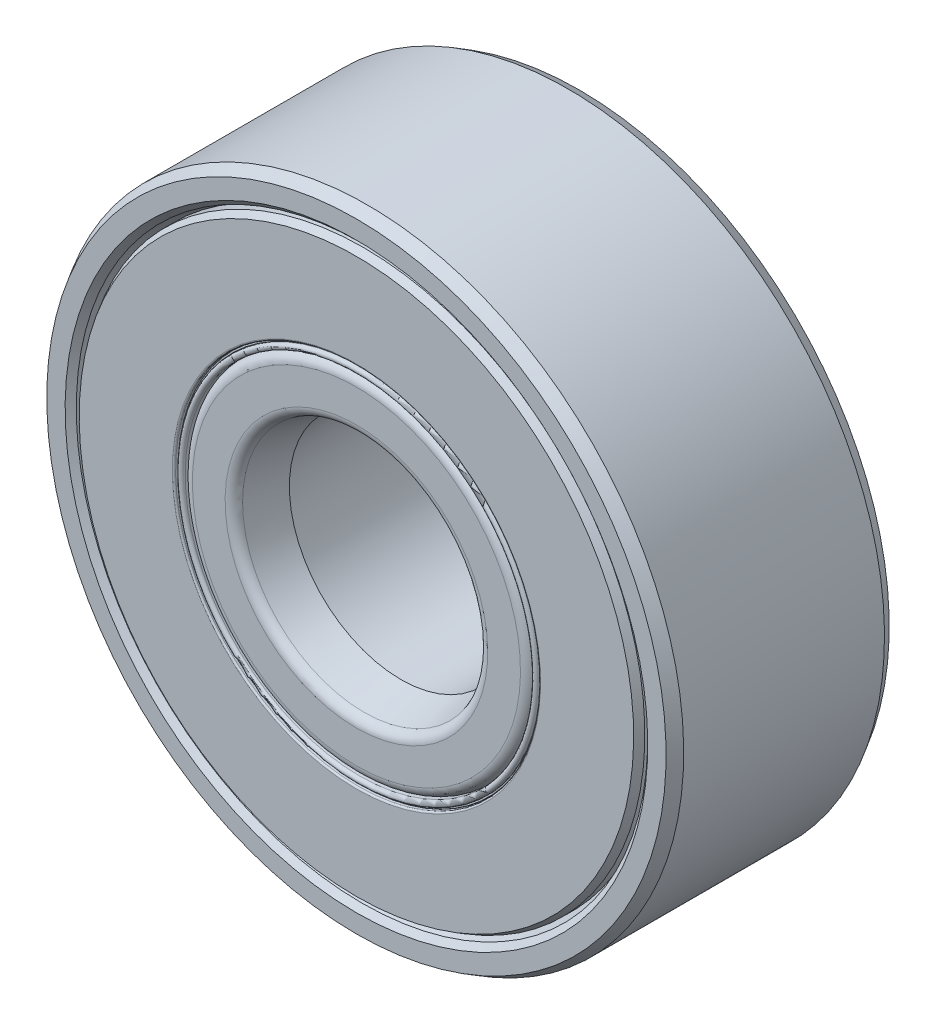
SolidWorks part; units mm, degrees
ref_plane "Front Plane" through (0, 0, 0) normal (0, 0, 1) x (1, 0, 0)
ref_plane "Top Plane" through (0, 0, 0) normal (0, 1, 0) x (1, 0, 0)
ref_plane "Right Plane" through (0, 0, 0) normal (1, 0, 0) x (0, 0, -1)
sketch "Sketch1" plane through (0, 0, 0) normal (0, 0, 1) x (1, 0, 0)
  line L0 (-8.5, 0) -> (8.5, 0) construction
  line L1 (-3, 0) -> (3, 0) construction
  circle A0 centre (0, 0) radius 3 construction
  circle A1 centre (0, 0) radius 8.5 construction
  point P3 (0, 0)
  point P6 (0, 0)
  point P7 (0, -3)
  point P11 (0, -8.5)
  point P12 (0, 3)
  point P13 (0, 8.5)
  dimension "OD" = 17
  dimension "ID" = 6
sketch "Sketch2" plane through (0, 0, 0) normal (1, 0, 0) x (0, 0, -1)
  line L0 (-3, 8.5) -> (3, 8.5) construction
  line L1 (0, 8.5) -> (0, -8.5) construction
  line L2 (2.7, 8.5) -> (-2.7, 8.5)
  line L3 (-2.7, 8.5) -> (-3, 8.3268)
  line L4 (-3, 8.3268) -> (-3, 7.8335)
  line L5 (-2.5245, 7.565) -> (-1.4774, 7.565)
  line L6 (2.5245, 7.565) -> (1.4774, 7.565)
  line L7 (3, 8.3268) -> (3, 7.8335)
  line L8 (2.7, 8.5) -> (3, 8.3268)
  line L9 (-1.4774, 7.565) -> (-1.4774, 7.8767) construction
  line L10 (-1.4774, 7.8767) -> (-1.4774, 8.1883) construction
  line L11 (0, 8.5) -> (0, -8.5) construction
  line L12 (-3, 0) -> (3, 0) construction
  line L13 (3, 3) -> (-3, 3) construction
  line L14 (-3, 3) -> (-3, -3) construction
  line L15 (-3, -3) -> (3, -3) construction
  line L16 (3, 8.5) -> (3, -8.5) construction
  line L17 (-1.4774, 8.1883) -> (-1.4774, 8.5) construction
  line L18 (-1.4774, 8.1883) -> (0, 8.1883) construction
  line L20 (-2.5245, 7.565) -> (-2.85, 7.6835)
  line L21 (-2.85, 7.6835) -> (-3, 7.8335)
  line L26 (2.85, 7.6835) -> (3, 7.8335)
  line L27 (2.5245, 7.565) -> (2.85, 7.6835)
  arc A0 (-1.4774, 7.565) -> (1.4774, 7.565) centre (0, 6.1258) cw
  circle A1 centre (0, 6.1258) radius 2.0625 construction
  point P17 (0, 0)
  point P21 (0, 8.5)
  point P30 (0, -3)
  dimension "Approx. Ball Dia." = 4.125
  dimension "Width" = 6
  dimension "For Shaft Diameter" = 6
  dimension "For Housing ID" = 17
  dimension "D4" = 15.13
  dimension "D2" = 20
  dimension "D5" = 45
  dimension "D1" = 30
  dimension "D6" = 0.3
  dimension "D7" = 0.15
sketch "Sketch3" plane through (0, 0, 0) normal (1, 0, 0) x (0, 0, -1)
  line L14 (-2.5245, 7.565) -> (-2.85, 7.6835) construction
  line L15 (-2.85, 7.6835) -> (-3, 7.8335) construction
  line L16 (-3, 8.3268) -> (-3, 7.8335) construction
  line L17 (-2.7, 8.5) -> (-3, 8.3268) construction
  line L18 (2.7, 8.5) -> (-2.7, 8.5) construction
  line L19 (2.7, 8.5) -> (3, 8.3268) construction
  line L20 (3, 8.3268) -> (3, 7.8335) construction
  line L21 (2.85, 7.6835) -> (3, 7.8335) construction
  line L22 (2.5245, 7.565) -> (2.85, 7.6835) construction
  line L23 (2.5245, 7.565) -> (1.4774, 7.565) construction
  line L24 (-2.5245, 7.565) -> (-1.4774, 7.565) construction
  line L25 (-2.5245, 7.565) -> (-2.85, 7.6835)
  line L26 (-2.85, 7.6835) -> (-3, 7.8335)
  line L27 (-3, 8.3268) -> (-3, 7.8335)
  line L28 (-2.7, 8.5) -> (-3, 8.3268)
  line L29 (2.7, 8.5) -> (-2.7, 8.5)
  line L30 (2.7, 8.5) -> (3, 8.3268)
  line L31 (3, 8.3268) -> (3, 7.8335)
  line L32 (2.85, 7.6835) -> (3, 7.8335)
  line L33 (2.5245, 7.565) -> (2.85, 7.6835)
  line L34 (2.5245, 7.565) -> (1.4774, 7.565)
  line L35 (-2.5245, 7.565) -> (-1.4774, 7.565)
  arc A2 (1.4774, 7.565) -> (-1.4774, 7.565) centre (0, 6.1258) ccw construction
  arc A3 (1.4774, 7.565) -> (-1.4774, 7.565) centre (0, 6.1258) ccw
revolve "Revolve1" add sketch "Sketch3" angle 360 about L12
sketch "Sketch4" plane through (0, 0, 0) normal (1, 0, 0) x (0, 0, -1)
  line L0 (0, 8.5) -> (0, -8.5) construction
  line L1 (0, 8.5) -> (0, -8.5) construction
  line L2 (-1.8039, 3) -> (-2.796, 3.2658)
  line L3 (-3, 3.5317) -> (-3, 4.4115)
  line L4 (3, -8.3268) -> (3, 8.3268) construction
  line L5 (-2.7248, 4.6867) -> (-1.4774, 4.6867)
  line L6 (-1.8039, 3) -> (1.8039, 3)
  line L7 (3, 8.3268) -> (3, 7.8335) construction
  line L8 (1.8039, 3) -> (2.796, 3.2658)
  line L9 (0, 8.1883) -> (0, 3) construction
  line L10 (3, 3.5317) -> (3, 4.4115)
  line L11 (2.7248, 4.6867) -> (1.4774, 4.6867)
  line L12 (1.8039, 3) -> (1.8039, 3.2658) construction
  line L13 (1.8039, 3.2658) -> (1.8039, 3.5317) construction
  line L14 (1.8039, 3.5317) -> (1.8039, 3.7975) construction
  line L15 (1.8039, 3.7975) -> (1.8039, 4.0633) construction
  circle A0 centre (0, 6.1258) radius 2.0625 construction
  arc A1 (1.4774, 4.6867) -> (-1.4774, 4.6867) centre (0, 6.1258) cw
  arc A2 (3, 4.4115) -> (2.7248, 4.6867) centre (2.7248, 4.4115) ccw
  arc A3 (-3, 4.4115) -> (-2.7248, 4.6867) centre (-2.7248, 4.4115) cw
  arc A4 (2.796, 3.2658) -> (3, 3.5317) centre (2.7248, 3.5317) ccw
  arc A5 (-2.796, 3.2658) -> (-3, 3.5317) centre (-2.7248, 3.5317) cw
  point P14 (3, 3.3205)
  point P36 (0, 4.0633)
  dimension "D1" = 15
revolve "Revolve2" add sketch "Sketch4" angle 360 about L12
sketch "Sketch5" plane through (0, 0, 0) normal (1, 0, 0) x (0, 0, -1)
  line L0 (-2.0625, 6.1258) -> (2.0625, 6.1258)
  arc A2 (-2.0625, 6.1258) -> (2.0625, 6.1258) centre (0, 6.1258) cw
  arc A3 (1.4774, 7.565) -> (-1.4774, 7.565) centre (0, 6.1258) ccw construction
revolve "Revolve3" add sketch "Sketch5" angle 360 about L0
pattern_circular "CirPattern1" count 7 over 360 about axis through (0, 0, 0) along (0, 0, 1) of bodies 104
sketch "Sketch6" plane through (0, 0, 0) normal (1, 0, 0) x (0, 0, -1)
  line L1 (-2.8095, 7.565) -> (-2.0625, 7.565)
  line L2 (-3, 7.455) -> (-3, 4.9507)
  line L3 (-2.956, 4.9067) -> (-2.0625, 4.9067)
  line L4 (-2.0625, 7.565) -> (-2.0625, 4.9067)
  line L5 (-3, 3.5317) -> (-3, 4.4115) construction
  line L6 (-2.7, 8.5) -> (-3, 8.3268) construction
  line L7 (0, 8.5) -> (0, 3) construction
  line L8 (2.956, 4.9067) -> (2.0625, 4.9067)
  line L9 (2.0625, 7.565) -> (2.0625, 4.9067)
  line L10 (2.8095, 7.565) -> (2.0625, 7.565)
  line L11 (3, 7.455) -> (3, 4.9507)
  line L13 (-2.7248, 4.6867) -> (-1.4774, 4.6867) construction
  line L14 (-3, 7.455) -> (-2.8095, 7.565)
  line L15 (-2.5245, 7.565) -> (-1.4774, 7.565) construction
  line L16 (3, 7.455) -> (2.8095, 7.565)
  arc A0 (-3, 4.9507) -> (-2.956, 4.9067) centre (-2.956, 4.9507) ccw
  circle A1 centre (0, 6.1258) radius 2.0625 construction
  arc A2 (3, 4.9507) -> (2.956, 4.9067) centre (2.956, 4.9507) cw
  point P26 (-3, 4.9067)
  dimension "D3" = 0.044
  dimension "D1" = 0.22
  dimension "D2" = 0.11
revolve "Revolve4" add sketch "Sketch6" angle 360 about L12
sketch "Sketch7" plane through (0, 0, 0) normal (1, 0, 0) x (0, 0, -1)
  line L3 (-2.0625, 4.9067) -> (-2.8423, 4.9067)
  line L4 (-2.956, 4.9067) -> (-2.0625, 4.9067) construction
  line L7 (0, 4.0633) -> (0, 3) construction
  line L8 (0, 8.5) -> (0, -8.5) construction
  line L21 (-2.8423, 4.9067) -> (-2.8965, 4.8971)
  line L22 (-2.8925, 4.8517) -> (-2.9175, 4.8517)
  line L23 (-2.9175, 4.6867) -> (-2.0625, 4.6867)
  line L24 (-2.0625, 4.6867) -> (-2.0625, 4.9067)
  line L25 (-2.7248, 4.6867) -> (-1.4774, 4.6867) construction
  line L26 (-3, 4.9507) -> (-3, 4.6867) construction
  line L27 (-3, 4.6867) -> (-2.9175, 4.6867) construction
  line L28 (-2.8423, 4.9067) -> (-2.8423, 4.8517) construction
  line L29 (-2.8423, 4.8517) -> (-2.8423, 4.7967) construction
  line L30 (-2.8423, 4.7967) -> (-2.8423, 4.7417) construction
  line L31 (-2.8423, 4.7417) -> (-2.8423, 4.6867) construction
  circle A2 centre (0, 6.1258) radius 2.0625 construction
  arc A9 (-2.8965, 4.8971) -> (-2.8925, 4.8517) centre (-2.8925, 4.8746) ccw
  arc A10 (-2.9175, 4.8517) -> (-2.9175, 4.6867) centre (-2.9175, 4.7692) ccw
  dimension "D1" = 0.025
  dimension "D2" = 10
revolve "Revolve5" add sketch "Sketch7" angle 360 about L12
equation "\"D4@Sketch2\"=\"OD@Sketch1\"*.89"
equation "\"D1@Sketch6\"=(\"OD@Sketch1\"-\"ID@Sketch1\")*.02"
equation "\"D2@Sketch6\"=\"D1@Sketch6\"*.5"
equation "\"D3@Sketch6\"=\"D1@Sketch6\"*.2"
equation "\"D6@Sketch2\"=\"Width@Sketch2\"*.05"
equation "\"D7@Sketch2\"=\"D6@Sketch2\"*.5"
equation "\"D1@CirPattern1\" =  ( pi * \"OD@Sketch1\" )  * .5625 / \"Approx. Ball Dia.@Sketch2\""
equation "\"Approx. Ball Dia.@Sketch2\"=(\"OD@Sketch1\"-\"ID@Sketch1\")*.5*.75"
